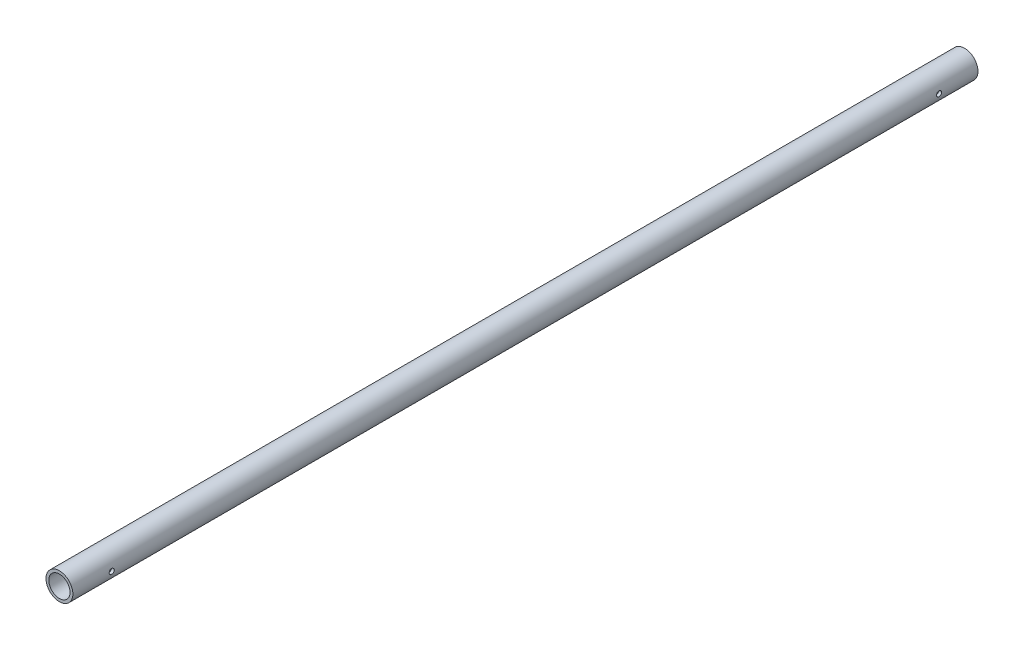
SolidWorks part; units mm, degrees
ref_plane "Front Plane" through (0, 0, 0) normal (0, 0, 1) x (1, 0, 0)
ref_plane "Top Plane" through (0, 0, 0) normal (0, 1, 0) x (1, 0, 0)
ref_plane "Right Plane" through (0, 0, 0) normal (1, 0, 0) x (0, 0, -1)
sketch "Sketch1" plane through (0, 0, 0) normal (0, 0, 1) x (1, 0, 0)
  circle A0 centre (0, 0) radius 12.065
  circle A1 centre (0, 0) radius 9.525
  dimension "D1" = 24.13
  dimension "D2" = 19.05
extrude "Boss-Extrude1" add sketch "Sketch1" along normal mid plane 812.8
sketch "Sketch2" plane through (0, 0, 406.4) normal (0, 0, 1) x (1, 0, 0)
  line L0 (0, 12.065) -> (0, -12.065) construction
  line L1 (-12.065, 0) -> (12.065, 0) construction
  circle A0 centre (0, 0) radius 12.065
  point P8 (0, 0)
sketch "Sketch3" plane through (0, 0, 0) normal (1, 0, 0) x (0, 0, -1)
  line L0 (0, 21.0529) -> (0, -22.6784) construction
  circle A0 centre (-371.475, 0) radius 2.286
  circle A1 centre (371.475, 0) radius 2.286
  dimension "D2" = 4.572
  dimension "D1" = 34.925
extrude "Cut-Extrude1" cut sketch "Sketch3" along normal up to next
